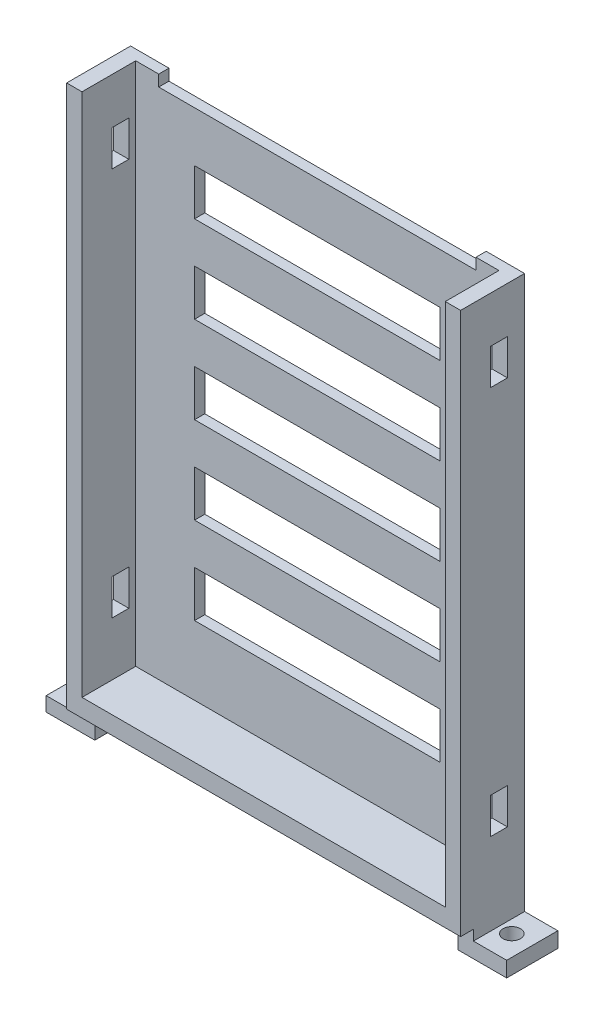
SolidWorks part; units mm, degrees
ref_plane "Спереди" through (0, 0, 0) normal (0, 0, 1) x (1, 0, 0)
ref_plane "Сверху" through (0, 0, 0) normal (0, 1, 0) x (1, 0, 0)
ref_plane "Справа" through (0, 0, 0) normal (1, 0, 0) x (0, 0, -1)
other "Configuration Table"
sketch "Эскиз1" plane through (0, 0, 0) normal (0, 0, 1) x (1, 0, 0)
  line L1 (-38.5, -62) -> (38.5, -62)
  line L2 (-38.5, -62) -> (-38.5, 44)
  line L3 (-38.5, 44) -> (38.5, 44)
  line L4 (38.5, -62) -> (38.5, 44)
extrude "Tray_floor_1" add sketch "Эскиз1" along normal blind 2
ref_plane "Плоскость1" through (0, 0, 2) normal (0, 0, 1) x (1, 0, 0)
sketch "Эскиз2" plane through (0, 0, 2) normal (0, 0, 1) x (1, 0, 0)
  line L0 (38.5, 44) -> (-38.5, 44) construction
  line L1 (-38.5, -62) -> (-35.5, -62)
  line L2 (-38.5, -62) -> (-38.5, 44)
  line L3 (-38.5, 44) -> (-35.5, 44)
  line L4 (-35.5, -62) -> (-35.5, 44)
extrude "Left_retainer_2" add sketch "Эскиз2" along normal blind 10.5
ref_plane "Плоскость2" through (0, 0, 2) normal (0, 0, 1) x (1, 0, 0)
sketch "Эскиз3" plane through (0, 0, 2) normal (0, 0, 1) x (1, 0, 0)
  line L0 (-35.5, -62) -> (38.5, -62) construction
  line L1 (35.5, -62) -> (38.5, -62)
  line L2 (35.5, -62) -> (35.5, 44)
  line L3 (35.5, 44) -> (38.5, 44)
  line L4 (38.5, -62) -> (38.5, 44)
extrude "Right_retainer_3" add sketch "Эскиз3" along normal blind 10.5
ref_plane "Плоскость3" through (0, 0, 2) normal (0, 0, 1) x (1, 0, 0)
sketch "Эскиз4" plane through (0, 0, 2) normal (0, 0, 1) x (1, 0, 0)
  line L0 (35.5, 44) -> (35.5, -62) construction
  line L1 (-35.5, -62) -> (35.5, -62)
  line L2 (-35.5, -62) -> (-35.5, -58.5)
  line L3 (-35.5, -58.5) -> (35.5, -58.5)
  line L4 (35.5, -62) -> (35.5, -58.5)
extrude "Front_retainer_4" add sketch "Эскиз4" along normal blind 10.5
sketch "Эскиз5" plane through (0, 0, 0) normal (0, 0, 1) x (1, 0, 0)
  line L0 (-38.5, -62) -> (38.5, -62) construction
  line L1 (-11, -70) -> (11, -70)
  line L2 (-11, -70) -> (-11, -62)
  line L3 (-11, -62) -> (11, -62)
  line L4 (11, -70) -> (11, -62)
extrude "Pull_handle_5" add sketch "Эскиз5" along normal blind 4
sketch "Эскиз6" plane through (0, 0, 0) normal (0, 0, 1) x (1, 0, 0)
  line L1 (-38.5, -65) -> (-35.5, -65)
  line L2 (-38.5, -65) -> (-38.5, -60)
  line L3 (-38.5, -60) -> (-35.5, -60)
  line L4 (-35.5, -65) -> (-35.5, -60)
extrude "Left_ear_bridge_6" add sketch "Эскиз6" along normal blind 10
sketch "Эскиз7" plane through (0, 0, 0) normal (0, 0, 1) x (1, 0, 0)
  line L0 (38.5, -62) -> (38.5, 44) construction
  line L1 (35.5, -65) -> (38.5, -65)
  line L2 (35.5, -65) -> (35.5, -60)
  line L3 (35.5, -60) -> (38.5, -60)
  line L4 (38.5, -65) -> (38.5, -60)
extrude "Right_ear_bridge_7" add sketch "Эскиз7" along normal blind 10
sketch "Эскиз8" plane through (0, 0, 0) normal (0, 0, 1) x (1, 0, 0)
  line L0 (-35.5, -65) -> (-35.5, -62) construction
  line L1 (-45, -67) -> (-35.5, -67)
  line L2 (-45, -67) -> (-45, -63.5)
  line L3 (-45, -63.5) -> (-35.5, -63.5)
  line L4 (-35.5, -67) -> (-35.5, -63.5)
extrude "Left_lock_ear_8" add sketch "Эскиз8" along normal blind 10
sketch "Эскиз9" plane through (0, 0, 0) normal (0, 0, 1) x (1, 0, 0)
  line L1 (35.5, -67) -> (45, -67)
  line L2 (35.5, -67) -> (35.5, -64)
  line L3 (35.5, -64) -> (45, -64)
  line L4 (45, -67) -> (45, -64)
extrude "Right_lock_ear_9" add sketch "Эскиз9" along normal blind 10
ref_plane "Плоскость4" through (0, -68, 0) normal (0, 1, 0) x (1, 0, 0)
sketch "Эскиз10" plane through (0, -68, 0) normal (0, 1, 0) x (1, 0, 0)
  circle A0 centre (-41, -5) radius 1.7
  circle A1 centre (41, -5) radius 1.7
extrude "Tray_lock_M3_clearance_10" cut sketch "Эскиз10" along normal blind 5
ref_plane "Плоскость5" through (0, 0, -1) normal (0, 0, 1) x (1, 0, 0)
sketch "Эскиз11" plane through (0, 0, -1) normal (0, 0, 1) x (1, 0, 0)
  line L1 (-24, -45) -> (24, -45)
  line L2 (-24, -45) -> (-24, -36)
  line L3 (-24, -36) -> (24, -36)
  line L4 (24, -45) -> (24, -36)
  line L5 (-24, -28) -> (24, -28)
  line L6 (-24, -28) -> (-24, -19)
  line L7 (-24, -19) -> (24, -19)
  line L8 (24, -28) -> (24, -19)
  line L9 (-24, -11) -> (24, -11)
  line L10 (-24, -11) -> (-24, -2)
  line L11 (-24, -2) -> (24, -2)
  line L12 (24, -11) -> (24, -2)
  line L13 (-24, 6) -> (24, 6)
  line L14 (-24, 6) -> (-24, 15)
  line L15 (-24, 15) -> (24, 15)
  line L16 (24, 6) -> (24, 15)
  line L17 (-24, 23) -> (24, 23)
  line L18 (-24, 23) -> (-24, 32)
  line L19 (-24, 32) -> (24, 32)
  line L20 (24, 23) -> (24, 32)
extrude "Tray_airflow_11" cut sketch "Эскиз11" along normal blind 4
ref_plane "Плоскость6" through (-40, 0, 0) normal (1, 0, 0) x (0, 0, -1)
sketch "Эскиз12" plane through (-40, 0, 0) normal (1, 0, 0) x (0, 0, -1)
  circle A0 centre (-5, -45.55) radius 1.65
  circle A1 centre (-5, 31.05) radius 1.65
extrude "Drive_side_M3_12" cut sketch "Эскиз12" along normal blind 80
ref_plane "Плоскость7" through (0, 0, -1) normal (0, 0, 1) x (1, 0, 0)
sketch "Эскиз13" plane through (0, 0, -1) normal (0, 0, 1) x (1, 0, 0)
  line L0 (50, -68) -> (-50, -68) construction
  line L1 (-7, -68) -> (7, -68)
  line L2 (-7, -68) -> (-7, -65)
  line L3 (-7, -65) -> (7, -65)
  line L4 (7, -68) -> (7, -65)
extrude "Handle_grip_13" cut sketch "Эскиз13" along normal blind 6
ref_plane "Плоскость8" through (0, 0, -1) normal (0, 0, 1) x (1, 0, 0)
sketch "Эскиз14" plane through (0, 0, -1) normal (0, 0, 1) x (1, 0, 0)
  line L0 (-38.5, 44) -> (-38.5, -62) construction
  line L1 (-46, -64.2) -> (-38.5, -64.2)
  line L2 (-46, -64.2) -> (-46, -60)
  line L3 (-46, -60) -> (-38.5, -60)
  line L4 (-38.5, -64.2) -> (-38.5, -60)
extrude "Left_flange_clearance_1" cut sketch "Эскиз14" along normal blind 15
ref_plane "Плоскость9" through (0, 0, -1) normal (0, 0, 1) x (1, 0, 0)
ref_plane "Плоскость10" through (-40, 0, 0) normal (1, 0, 0) x (0, 0, -1)
sketch "Эскиз16" plane through (-40, 0, 0) normal (1, 0, 0) x (0, 0, -1)
  line L1 (-3.35, -48) -> (-6.65, -48)
  line L2 (-3.35, -48) -> (-3.35, -41)
  line L3 (-3.35, -41) -> (-6.65, -41)
  line L4 (-6.65, -48) -> (-6.65, -41)
extrude "Front_adjustable_M3_slot_1" cut sketch "Эскиз16" along normal blind 80
ref_plane "Плоскость11" through (-40, 0, 0) normal (1, 0, 0) x (0, 0, -1)
sketch "Эскиз17" plane through (-40, 0, 0) normal (1, 0, 0) x (0, 0, -1)
  line L1 (-3.35, 28) -> (-6.65, 28)
  line L2 (-3.35, 28) -> (-3.35, 35)
  line L3 (-3.35, 35) -> (-6.65, 35)
  line L4 (-6.65, 28) -> (-6.65, 35)
extrude "Rear_adjustable_M3_slot_2" cut sketch "Эскиз17" along normal blind 80
ref_plane "Плоскость12" through (0, 0, -1) normal (0, 0, 1) x (1, 0, 0)
sketch "Эскиз18" plane through (0, 0, -1) normal (0, 0, 1) x (1, 0, 0)
  line L1 (-31, 41.8) -> (31, 41.8)
  line L2 (-31, 41.8) -> (-31, 45)
  line L3 (-31, 45) -> (31, 45)
  line L4 (31, 41.8) -> (31, 45)
extrude "SATA_plug_lower_clearance_301" cut sketch "Эскиз18" along normal blind 5
